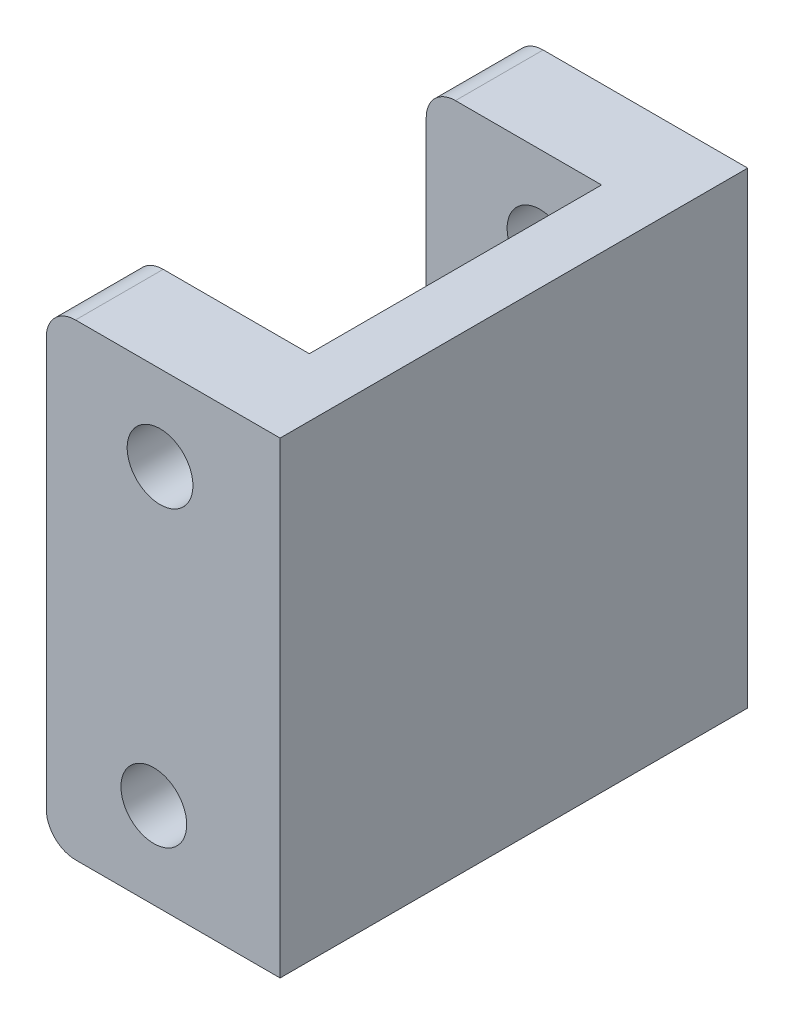
SolidWorks part; units mm, degrees
ref_plane "Front Plane" through (0, 0, 0) normal (0, 0, 1) x (1, 0, 0)
ref_plane "Top Plane" through (0, 0, 0) normal (0, 1, 0) x (1, 0, 0)
ref_plane "Right Plane" through (0, 0, 0) normal (1, 0, 0) x (0, 0, -1)
sketch "Sketch1" plane through (0, 0, 0) normal (1, 0, 0) x (0, 0, -1)
  line L1 (-12.7, 25.4) -> (12.7, 25.4)
  line L2 (-12.7, 25.4) -> (-12.7, -25.4)
  line L3 (-12.7, -25.4) -> (12.7, -25.4)
  line L4 (12.7, 25.4) -> (12.7, -25.4)
  line L5 (-12.7, 25.4) -> (12.7, -25.4) construction
  line L6 (-12.7, -25.4) -> (12.7, 25.4) construction
  point P0 (0, 0)
  dimension "D1" = 25.4
  dimension "D2" = 50.8
extrude "Boss-Extrude1" add sketch "Sketch1" along normal mid plane 6.35
sketch "Sketch3" plane through (0, 0, 0) normal (0, 0, 1) x (1, 0, 0)
  line L4 (-3.175, 25.4) -> (-3.175, -25.4)
  line L5 (-3.175, -25.4) -> (3.175, -25.4)
  line L6 (3.175, -25.4) -> (3.175, 25.4)
  line L7 (3.175, 25.4) -> (-3.175, 25.4)
  line L8 (-3.175, 25.4) -> (-3.175, -25.4)
  line L9 (-3.175, -25.4) -> (3.175, -25.4)
  line L10 (3.175, -25.4) -> (3.175, 25.4)
  line L11 (3.175, 25.4) -> (-3.175, 25.4)
  dimension "D1" = 0
sketch "Sketch4" plane through (0, 0, 12.7) normal (0, 0, 1) x (1, 0, 0)
  line L4 (-3.175, 25.4) -> (-3.175, -25.4)
  line L5 (-3.175, -25.4) -> (3.175, -25.4)
  line L6 (3.175, -25.4) -> (3.175, 25.4)
  line L7 (3.175, 25.4) -> (-3.175, 25.4)
  line L8 (-3.175, 25.4) -> (-3.175, -25.4)
  line L9 (-3.175, -25.4) -> (3.175, -25.4)
  line L10 (3.175, -25.4) -> (3.175, 25.4)
  line L11 (3.175, 25.4) -> (-3.175, 25.4)
  dimension "D1" = 0
extrude "Boss-Extrude2" add sketch "Sketch4" along normal blind 12.7
sketch "Sketch5" plane through (3.175, 0, 0) normal (1, 0, 0) x (0, 0, -1)
  line L0 (-25.4, -25.4) -> (12.7, -25.4) construction
  line L1 (-25.4, 25.4) -> (-15.875, 25.4)
  line L2 (-25.4, 25.4) -> (-25.4, -25.4)
  line L3 (-25.4, -25.4) -> (-15.875, -25.4)
  line L4 (-15.875, 25.4) -> (-15.875, -25.4)
  dimension "D1" = 9.525
extrude "Boss-Extrude3" add sketch "Sketch5" against normal blind 25.4
mirror "Mirror1" about plane through (0, 0, 0) normal (0, 0, 1) of "Boss-Extrude2", "Boss-Extrude3"
hole_wizard "1/4 Clearance Hole1" positions "3DSketch1" profile "Sketch6" hole size "1/4" standard "ANSI Inch" end condition through all
sketch3d "3DSketch1"
  point P0 (-9.8668, 16.191, 25.4)
  point P2 (-10.5441, -16.0417, 25.4)
sketch "Sketch6" plane through (-9.8668, 16.191, 25.4) normal (1, 0, 0) x (0, -1, 0)
  line L0 (0, 0) -> (0, 50.8)
  line L1 (0, 50.8) -> (3.5712, 50.8)
  line L2 (3.5712, 50.8) -> (3.5712, 0)
  line L5 (3.5712, 0) -> (0, 0)
  line L11 (0, -6.35) -> (0, 107.95) construction
  dimension "Thru Hole Dia." = 7.1425
  dimension "Thru Hole Depth" = 50.8
fillet "Fillet1" radius 3.175 4 edges at (-22.225, -25.4, -20.6375) (-22.225, 25.4, -20.6375) (-22.225, -25.4, 20.6375) (-22.225, 25.4, 20.6375)
